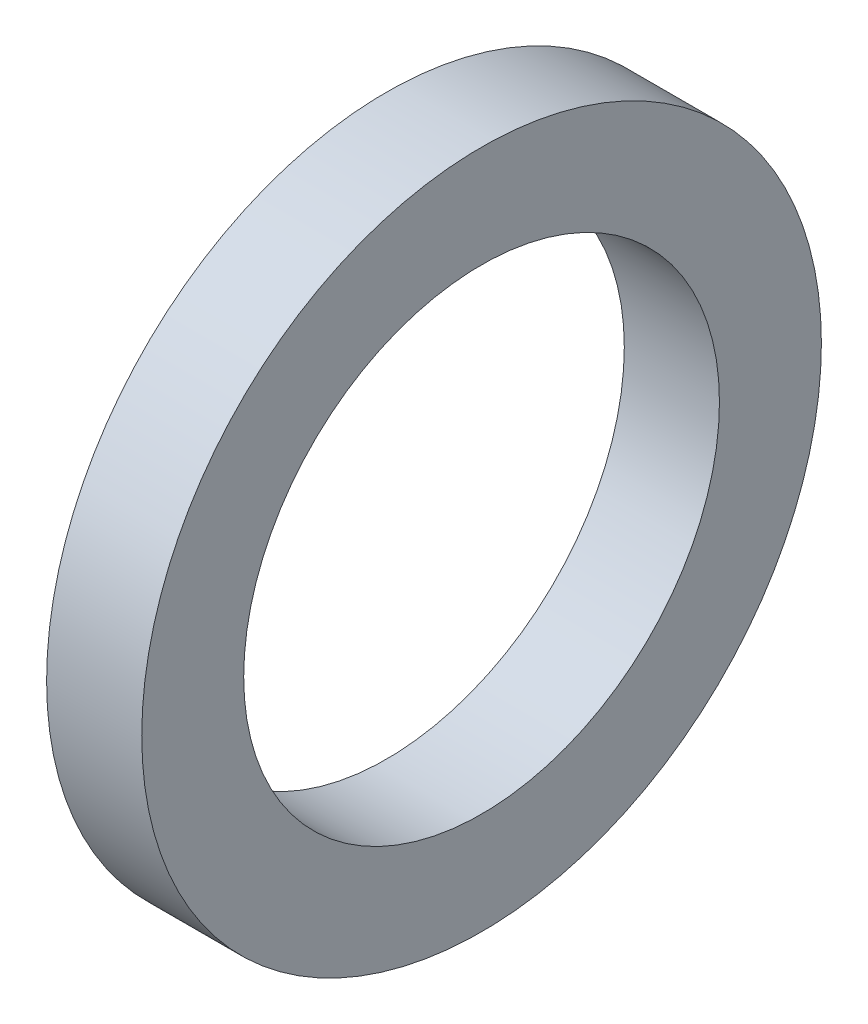
SolidWorks part; units mm, degrees
material "Rubber"
ref_plane "Front Plane" through (0, 0, 0) normal (0, 0, 1) x (1, 0, 0)
ref_plane "Top Plane" through (0, 0, 0) normal (0, 1, 0) x (1, 0, 0)
ref_plane "Right Plane" through (0, 0, 0) normal (1, 0, 0) x (0, 0, -1)
sketch "Sketch1" plane through (0, 0, 0) normal (1, 0, 0) x (0, 0, -1)
  circle A0 centre (0, 0) radius 25
  circle A1 centre (0, 0) radius 17.5
  dimension "D1" = 35
  dimension "D2" = 50
extrude "Boss-Extrude1" add sketch "Sketch1" along normal blind 7
